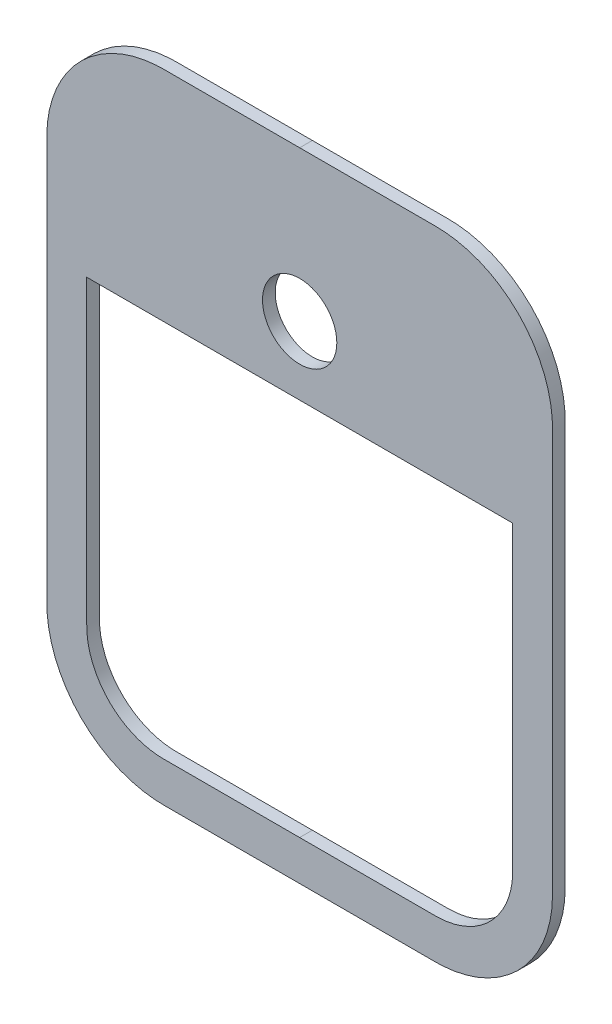
SolidWorks part; units mm, degrees
material "Фанера"
ref_plane "Front Plane" through (0, 0, 0) normal (0, 0, 1) x (1, 0, 0)
ref_plane "Top Plane" through (0, 0, 0) normal (0, 1, 0) x (1, 0, 0)
ref_plane "Right Plane" through (0, 0, 0) normal (1, 0, 0) x (0, 0, -1)
sketch "Эскиз1" plane through (0, 0, 0) normal (0, 0, 1) x (1, 0, 0)
  line L0 (-47, 88.5735) -> (47, 88.5735)
  circle A1 centre (0, 103.6369) radius 5.3081 construction
  circle A2 centre (0, 103.6369) radius 8.2
  spline S2 degree 3 poles (0, -3.0157) (10, -3.0157) (20, -3.0157) (31.6362, -3.0157) (34.9087, -2.6935) (39.6288, -1.2616) (43.9788, 1.0635) (47.7917, 4.1926) (50.9208, 8.0055) (53.2459, 12.3555) (54.6778, 17.0756) (55, 20.3481) (55, 51.6579) (55, 81.3315) (55, 112.6414) (54.6778, 115.9139) (53.2459, 120.6339) (50.9208, 124.984) (47.7917, 128.7968) (43.9788, 131.926) (39.6288, 134.2511) (34.9087, 135.6829) (31.6362, 136.0052) (20, 136.0052) (10, 136.0052) (0, 136.0052) knots 0 0 0 0 0.131833 0.131833 0.153404 0.174975 0.196546 0.218117 0.239689 0.26126 0.282831 0.304402 0.304402 0.695598 0.695598 0.717169 0.73874 0.760311 0.781883 0.803454 0.825025 0.846596 0.868167 0.868167 1 1 1 1 construction
  spline S3 degree 3 poles (0, 136.0052) (-10, 136.0052) (-20, 136.0052) (-31.6362, 136.0052) (-34.9087, 135.6829) (-39.6288, 134.2511) (-43.9788, 131.926) (-47.7917, 128.7968) (-50.9208, 124.984) (-53.2459, 120.6339) (-54.6778, 115.9139) (-55, 112.6414) (-55, 81.3315) (-55, 51.6579) (-55, 20.3481) (-54.6778, 17.0756) (-53.2459, 12.3555) (-50.9208, 8.0055) (-47.7917, 4.1926) (-43.9788, 1.0635) (-39.6288, -1.2616) (-34.9087, -2.6935) (-31.6362, -3.0157) (-20, -3.0157) (-10, -3.0157) (0, -3.0157) knots 0 0 0 0 0.131833 0.131833 0.153404 0.174975 0.196546 0.218117 0.239689 0.26126 0.282831 0.304402 0.304402 0.695598 0.695598 0.717169 0.73874 0.760311 0.781883 0.803454 0.825025 0.846596 0.868167 0.868167 1 1 1 1 construction
  spline S4 degree 1 poles (0, 136.8052) (0, -3.8157) knots 0 0 1 1 construction
  spline S5 degree 1 poles (0, -3.8157) (0, 136.8052) knots 0 0 1 1 construction
  spline S6 degree 3 poles (0, 136.8052) (-2.3704, 136.8052) (-7.1113, 136.805) (-14.2223, 136.8057) (-20.1493, 136.8036) (-24.8883, 136.8079) (-27.856, 136.7971) (-30.2168, 136.8192) (-32.6834, 136.7208) (-35.7037, 136.2543) (-39.2284, 135.1921) (-43.6745, 133.1222) (-48.5978, 129.3899) (-52.2728, 124.4241) (-54.2918, 119.9544) (-55.3122, 116.4178) (-55.7479, 113.392) (-55.8096, 110.9252) (-55.7945, 108.5784) (-55.8018, 105.6039) (-55.7989, 100.8675) (-55.8004, 94.9393) (-55.7999, 87.8287) (-55.8001, 78.3468) (-55.8, 66.4947) (-55.8001, 54.6427) (-55.7999, 45.1608) (-55.8004, 38.0502) (-55.7989, 32.1219) (-55.8018, 27.3856) (-55.7945, 24.4111) (-55.8096, 22.0643) (-55.7479, 19.5975) (-55.3122, 16.5716) (-54.2918, 13.0351) (-52.2728, 8.5654) (-48.5978, 3.5995) (-43.6745, -0.1327) (-39.2284, -2.2026) (-35.7037, -3.2649) (-32.6834, -3.7314) (-30.2168, -3.8297) (-27.856, -3.8076) (-24.8883, -3.8184) (-20.1493, -3.8142) (-14.2223, -3.8162) (-7.1113, -3.8156) (-2.3704, -3.8157) (0, -3.8157) knots 0 0 0 0 0.03125 0.0625 0.09375 0.109375 0.125 0.132812 0.140625 0.15625 0.171875 0.1875 0.21875 0.25 0.265625 0.28125 0.296875 0.304688 0.3125 0.328125 0.34375 0.375 0.40625 0.4375 0.5 0.5625 0.59375 0.625 0.65625 0.671875 0.6875 0.695312 0.703125 0.71875 0.734375 0.75 0.78125 0.8125 0.828125 0.84375 0.859375 0.867188 0.875 0.890625 0.90625 0.9375 0.96875 1 1 1 1
  spline S7 degree 3 poles (0, -3.8157) (2.3704, -3.8157) (7.1113, -3.8156) (14.2223, -3.8162) (20.1493, -3.8142) (24.8883, -3.8184) (27.856, -3.8076) (30.2168, -3.8297) (32.6834, -3.7314) (35.7037, -3.2649) (39.2284, -2.2026) (43.6745, -0.1327) (48.5978, 3.5995) (52.2728, 8.5654) (54.2918, 13.0351) (55.3122, 16.5716) (55.7479, 19.5975) (55.8096, 22.0643) (55.7945, 24.4111) (55.8018, 27.3856) (55.7989, 32.1219) (55.8004, 38.0502) (55.7999, 45.1608) (55.8001, 54.6427) (55.8, 66.4947) (55.8001, 78.3468) (55.7999, 87.8287) (55.8004, 94.9393) (55.7989, 100.8675) (55.8018, 105.6039) (55.7945, 108.5784) (55.8096, 110.9252) (55.7479, 113.392) (55.3122, 116.4178) (54.2918, 119.9544) (52.2728, 124.4241) (48.5978, 129.3899) (43.6745, 133.1222) (39.2284, 135.1921) (35.7037, 136.2543) (32.6834, 136.7208) (30.2168, 136.8192) (27.856, 136.7971) (24.8883, 136.8079) (20.1493, 136.8036) (14.2223, 136.8057) (7.1113, 136.805) (2.3704, 136.8052) (0, 136.8052) knots 0 0 0 0 0.03125 0.0625 0.09375 0.109375 0.125 0.132812 0.140625 0.15625 0.171875 0.1875 0.21875 0.25 0.265625 0.28125 0.296875 0.304688 0.3125 0.328125 0.34375 0.375 0.40625 0.4375 0.5 0.5625 0.59375 0.625 0.65625 0.671875 0.6875 0.695312 0.703125 0.71875 0.734375 0.75 0.78125 0.8125 0.828125 0.84375 0.859375 0.867188 0.875 0.890625 0.90625 0.9375 0.96875 1 1 1 1
  spline S8 degree 1 poles (0, 128.0052) (0, 4.9843) knots 0 0 1 1 construction
  spline S9 degree 1 poles (0, 4.9843) (0, 128.0052) knots 0 0 1 1 construction
  spline S10 degree 3 poles (0, 128.0052) (-2.3704, 128.0052) (-7.1113, 128.0052) (-13.0373, 128.0052) (-17.7782, 128.0052) (-20.7411, 128.0052) (-23.1118, 128.0052) (-24.8889, 128.0052) (-26.6692, 128.0052) (-28.1432, 128.0051) (-29.1936, 128.0052) (-29.6934, 128.0051) (-30.02, 128.0053) (-30.1904, 128.0046) (-30.4571, 128) (-30.8539, 127.9857) (-31.3599, 127.9543) (-31.9612, 127.8952) (-32.7609, 127.788) (-34.1451, 127.5265) (-36.0814, 126.9418) (-39.0103, 125.5784) (-42.2541, 123.1194) (-44.6763, 119.8468) (-46.0055, 116.9027) (-46.568, 114.9601) (-46.8135, 113.5726) (-46.9115, 112.7716) (-46.9636, 112.1695) (-46.9892, 111.6641) (-46.9977, 111.3153) (-46.9996, 111.1342) (-47, 111.0417) (-47, 110.8408) (-47, 110.4912) (-47, 109.9057) (-47, 109.1615) (-47, 108.2737) (-47, 107.0881) (-47, 105.0142) (-47, 102.0511) (-47, 98.4955) (-47, 94.2992) (-47, 90.6956) (-47, 85.9548) (-47, 80.6693) (-47, 73.606) (-47, 66.4947) (-47, 59.3835) (-47, 52.2722) (-47, 45.1609) (-47, 39.2349) (-47, 34.494) (-47, 30.9384) (-47, 27.9753) (-47, 25.9014) (-47, 24.7158) (-47, 23.828) (-47, 23.0837) (-47, 22.4982) (-47, 22.1486) (-47, 21.9478) (-46.9996, 21.8553) (-46.9977, 21.6741) (-46.9892, 21.3254) (-46.9636, 20.82) (-46.9115, 20.2179) (-46.8135, 19.4169) (-46.568, 18.0294) (-46.0055, 16.0868) (-44.6763, 13.1427) (-42.2541, 9.87) (-39.0103, 7.411) (-36.0814, 6.0477) (-34.1451, 5.4629) (-32.7609, 5.2015) (-31.9612, 5.0943) (-31.3599, 5.0352) (-30.8539, 5.0038) (-30.4571, 4.9895) (-30.1904, 4.9849) (-30.02, 4.9842) (-29.6934, 4.9844) (-29.1936, 4.9843) (-28.1432, 4.9843) (-26.6692, 4.9843) (-24.8889, 4.9843) (-23.1118, 4.9843) (-20.7411, 4.9843) (-17.7782, 4.9843) (-13.0373, 4.9843) (-7.1113, 4.9843) (-2.3704, 4.9843) (0, 4.9843) knots 0 0 0 0 0.03125 0.0625 0.078125 0.09375 0.101562 0.109375 0.117188 0.125 0.128906 0.130859 0.131836 0.132812 0.134766 0.136719 0.140625 0.144531 0.148438 0.15625 0.171875 0.1875 0.21875 0.25 0.265625 0.28125 0.289062 0.292969 0.296875 0.300781 0.302734 0.303711 0.304199 0.304688 0.306641 0.308594 0.3125 0.316406 0.320312 0.328125 0.34375 0.359375 0.375 0.39907 0.406882 0.4375 0.46875 0.5 0.53125 0.5625 0.59375 0.625 0.640625 0.65625 0.671875 0.679688 0.683594 0.6875 0.691406 0.693359 0.695312 0.695801 0.696289 0.697266 0.699219 0.703125 0.707031 0.710938 0.71875 0.734375 0.75 0.78125 0.8125 0.828125 0.84375 0.851562 0.855469 0.859375 0.863281 0.865234 0.867188 0.868164 0.869141 0.871094 0.875 0.882812 0.890625 0.898438 0.90625 0.921875 0.9375 0.96875 1 1 1 1
  spline S11 degree 3 poles (0, 4.9843) (2.3704, 4.9843) (7.1113, 4.9843) (13.0373, 4.9843) (17.7782, 4.9843) (20.7411, 4.9843) (23.1118, 4.9843) (24.8889, 4.9843) (26.6692, 4.9843) (28.1432, 4.9843) (29.1936, 4.9843) (29.6934, 4.9844) (30.02, 4.9842) (30.1904, 4.9849) (30.4571, 4.9895) (30.8539, 5.0038) (31.3599, 5.0352) (31.9612, 5.0943) (32.7609, 5.2015) (34.1451, 5.4629) (36.0814, 6.0477) (39.0103, 7.411) (42.2541, 9.87) (44.6763, 13.1427) (46.0055, 16.0868) (46.568, 18.0294) (46.8135, 19.4169) (46.9115, 20.2179) (46.9636, 20.82) (46.9892, 21.3254) (46.9977, 21.6741) (46.9996, 21.8553) (47, 21.9478) (47, 22.1486) (47, 22.4982) (47, 23.0837) (47, 23.828) (47, 24.7158) (47, 25.9014) (47, 27.9753) (47, 30.9384) (47, 34.494) (47, 39.2349) (47, 45.1609) (47, 52.2722) (47, 59.3835) (47, 66.4947) (47, 73.606) (47, 80.6693) (47, 85.9548) (47, 90.6956) (47, 94.2992) (47, 98.4955) (47, 102.0511) (47, 105.0142) (47, 107.0881) (47, 108.2737) (47, 109.1615) (47, 109.9057) (47, 110.4912) (47, 110.8408) (47, 111.0417) (46.9996, 111.1342) (46.9977, 111.3153) (46.9892, 111.6641) (46.9636, 112.1695) (46.9115, 112.7716) (46.8135, 113.5726) (46.568, 114.9601) (46.0055, 116.9027) (44.6763, 119.8468) (42.2541, 123.1194) (39.0103, 125.5784) (36.0814, 126.9418) (34.1451, 127.5265) (32.7609, 127.788) (31.9612, 127.8952) (31.3599, 127.9543) (30.8539, 127.9857) (30.4571, 128) (30.1904, 128.0046) (30.02, 128.0053) (29.6934, 128.0051) (29.1936, 128.0052) (28.1432, 128.0051) (26.6692, 128.0052) (24.8889, 128.0052) (23.1118, 128.0052) (20.7411, 128.0052) (17.7782, 128.0052) (13.0373, 128.0052) (7.1113, 128.0052) (2.3704, 128.0052) (0, 128.0052) knots 0 0 0 0 0.03125 0.0625 0.078125 0.09375 0.101562 0.109375 0.117188 0.125 0.128906 0.130859 0.131836 0.132812 0.134766 0.136719 0.140625 0.144531 0.148438 0.15625 0.171875 0.1875 0.21875 0.25 0.265625 0.28125 0.289062 0.292969 0.296875 0.300781 0.302734 0.303711 0.304199 0.304688 0.306641 0.308594 0.3125 0.316406 0.320312 0.328125 0.34375 0.359375 0.375 0.40625 0.4375 0.46875 0.5 0.53125 0.5625 0.593118 0.60093 0.625 0.640625 0.65625 0.671875 0.679688 0.683594 0.6875 0.691406 0.693359 0.695312 0.695801 0.696289 0.697266 0.699219 0.703125 0.707031 0.710938 0.71875 0.734375 0.75 0.78125 0.8125 0.828125 0.84375 0.851562 0.855469 0.859375 0.863281 0.865234 0.867188 0.868164 0.869141 0.871094 0.875 0.882812 0.890625 0.898438 0.90625 0.921875 0.9375 0.96875 1 1 1 1
  dimension "D1" = 16.4
  dimension "D2" = 0.8
  dimension "D3" = 8
extrude "Бобышка-Вытянуть1" add sketch "Эскиз1" along normal mid plane 2.8 contours L0 S11 S10 A2 | S6 S7 S11 S10
